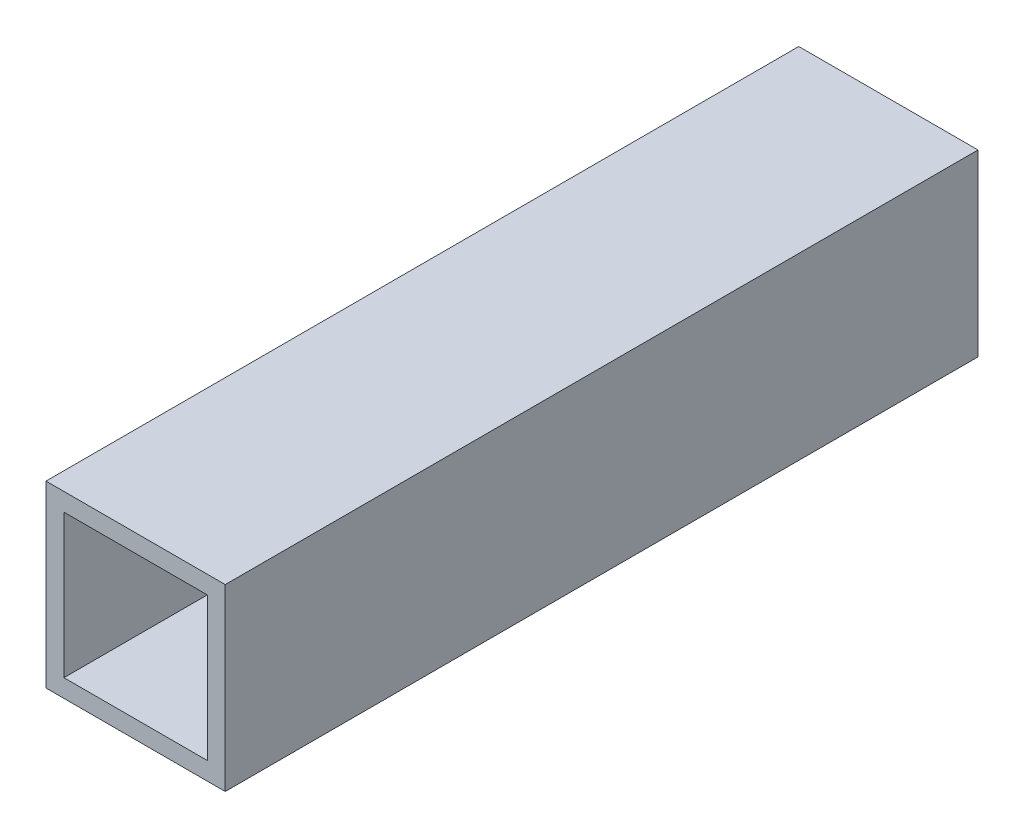
SolidWorks part; units mm, degrees
material "3.0205 (EN-AW 1200)"
ref_plane "前视基准面" through (0, 0, 0) normal (0, 0, 1) x (1, 0, 0)
ref_plane "上视基准面" through (0, 0, 0) normal (0, 1, 0) x (1, 0, 0)
ref_plane "右视基准面" through (0, 0, 0) normal (1, 0, 0) x (0, 0, -1)
sketch "草图1" plane through (0, 0, 0) normal (0, 0, 1) x (1, 0, 0)
  line L1 (-10, -10) -> (10, -10)
  line L2 (-10, -10) -> (-10, 10)
  line L3 (-10, 10) -> (10, 10)
  line L4 (10, -10) -> (10, 10)
  line L5 (-10, -10) -> (10, 10) construction
  line L6 (-10, 10) -> (10, -10) construction
  line L7 (-8, -8) -> (8, -8)
  line L8 (-8, -8) -> (-8, 8)
  line L9 (-8, 8) -> (8, 8)
  line L10 (8, -8) -> (8, 8)
  line L11 (-8, -8) -> (8, 8) construction
  line L12 (-8, 8) -> (8, -8) construction
  point P0 (0, 0)
  point P6 (0, 0)
  dimension "D1" = 16
  dimension "D2" = 20
  dimension "D3" = 20
extrude "凸台-拉伸1" add sketch "草图1" along normal blind 84
